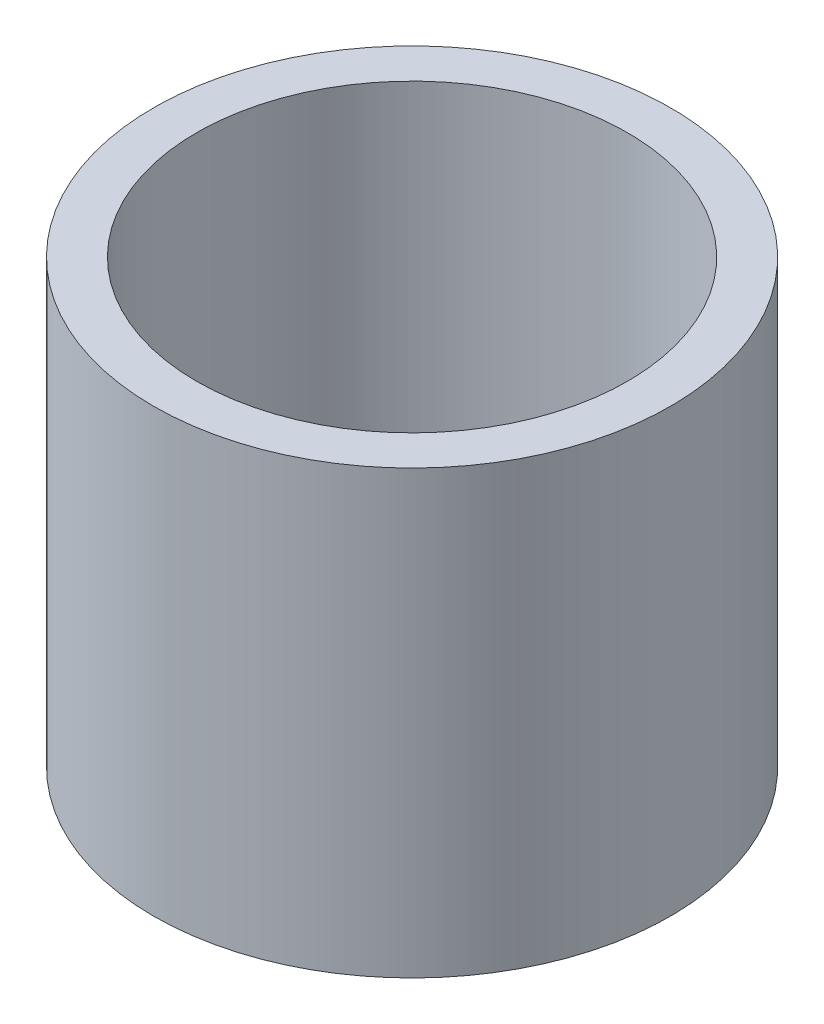
SolidWorks part; units mm, degrees
material "Plain Carbon Steel"
ref_plane "Front Plane" through (0, 0, 0) normal (0, 0, 1) x (1, 0, 0)
ref_plane "Top Plane" through (0, 0, 0) normal (0, 1, 0) x (1, 0, 0)
ref_plane "Right Plane" through (0, 0, 0) normal (1, 0, 0) x (0, 0, -1)
sketch "Sketch1" plane through (0, 0, 0) normal (0, 1, 0) x (1, 0, 0)
  circle A0 centre (0, 0) radius 12
  circle A1 centre (0, 0) radius 10
  dimension "D1" = 20
  dimension "D2" = 24
extrude "Boss-Extrude1" add sketch "Sketch1" along normal mid plane 20.5
